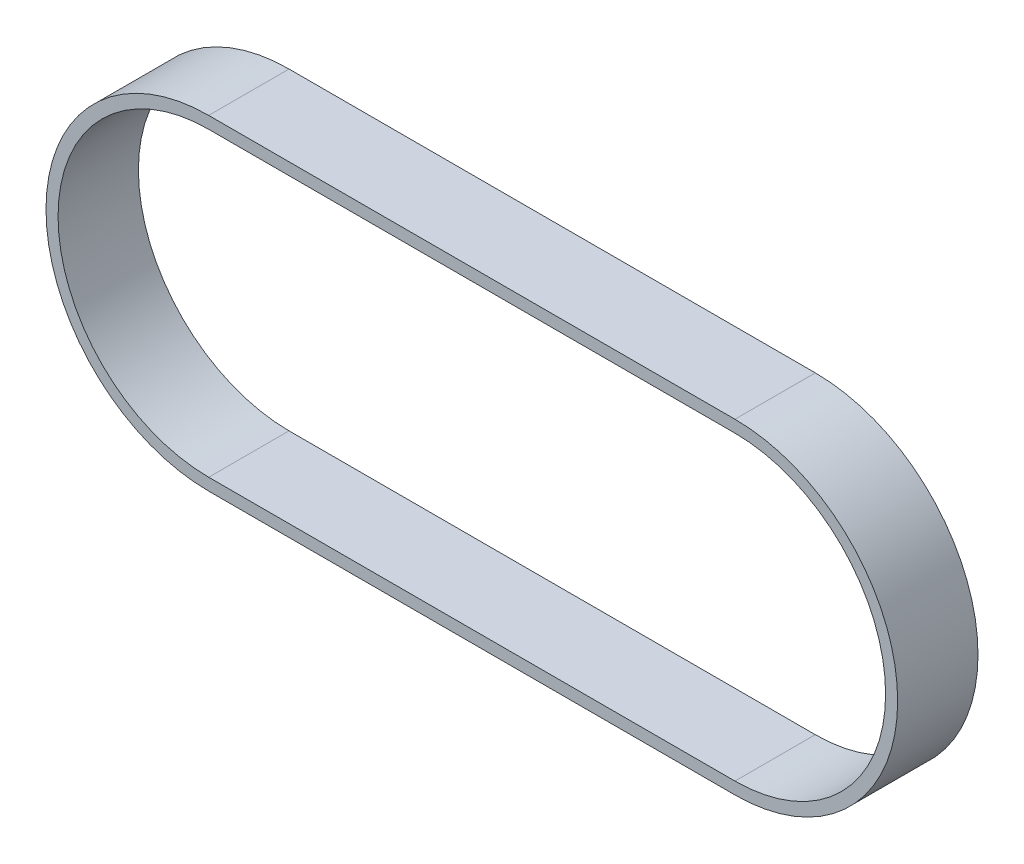
SolidWorks part; units mm, degrees
ref_plane "前视基准面" through (0, 0, 0) normal (0, 0, 1) x (1, 0, 0)
ref_plane "上视基准面" through (0, 0, 0) normal (0, 1, 0) x (1, 0, 0)
ref_plane "右视基准面" through (0, 0, 0) normal (1, 0, 0) x (0, 0, -1)
sketch "草图1" plane through (0, 0, 0) normal (0, 0, 1) x (1, 0, 0)
  line L1 (0, 37.5) -> (131, 37.5)
  line L2 (0, -37.5) -> (131, -37.5)
  arc A0 (0, 37.5) -> (0, -37.5) centre (0, 0) ccw
  arc A1 (131, -37.5) -> (131, 37.5) centre (131, 0) ccw
  dimension "D1" = 131
  dimension "D2" = 131
  dimension "D3" = 131
extrude "拉伸-薄壁1" add sketch "草图1" along normal blind 20 thin thin type one direction wall 3
